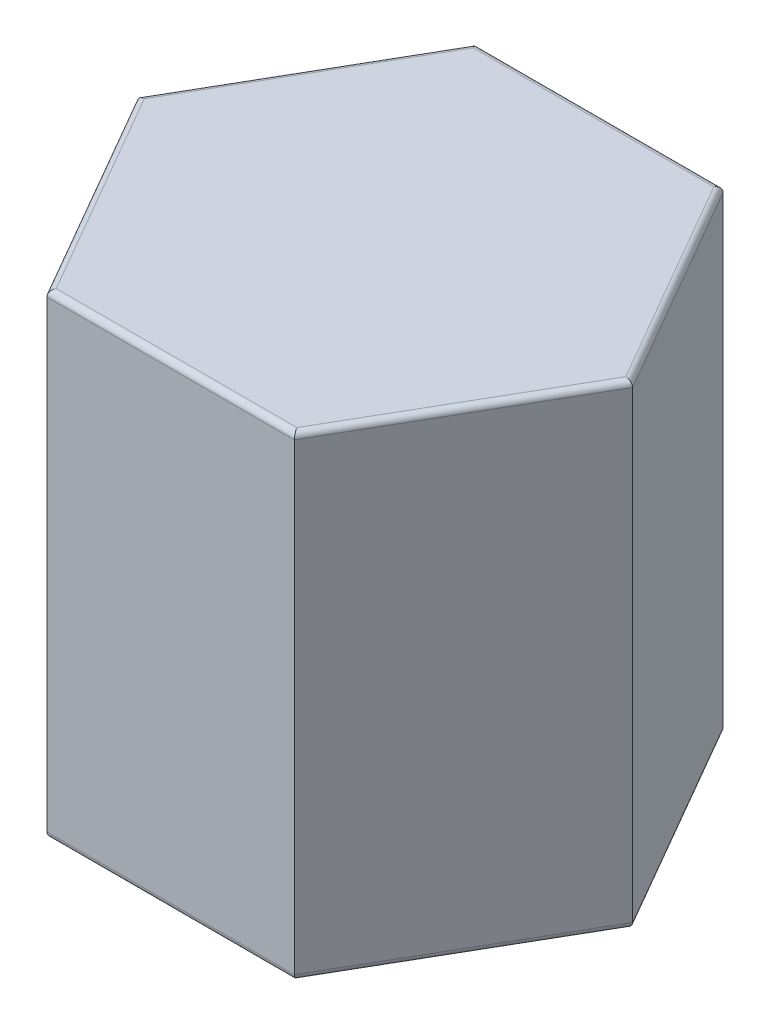
SolidWorks part; units mm, degrees
ref_plane "Front Plane" through (0, 0, 0) normal (1, 0, 0) x (0, 1, 0)
ref_plane "Top Plane" through (0, 0, 0) normal (0, 0, 1) x (0, 1, 0)
ref_plane "Right Plane" through (0, 0, 0) normal (0, 1, 0) x (-1, 0, 0)
sketch "Sketch1" plane through (0, 0, 0) normal (0, 1, 0) x (-1, 0, 0)
  line L0 (-10.4236, 18.0542) -> (10.4217, 18.0542)
  line L1 (10.4217, 18.0542) -> (20.8443, 0.0016)
  line L2 (20.8443, 0.0016) -> (10.4217, -18.0509)
  line L3 (10.4217, -18.0509) -> (-10.4236, -18.0509)
  line L4 (-10.4236, -18.0509) -> (-20.8463, 0.0016)
  line L5 (-20.8463, 0.0016) -> (-10.4236, 18.0542)
extrude "Boss-Extrude1" add sketch "Sketch1" along normal blind 40
fillet "Fillet1" radius 0.5 12 edges at (15.6349, 0, 9.0279) (15.6349, 0, -9.0246) (0.001, 0, -18.0509) (-15.633, 0, -9.0246) (-15.633, 0, 9.0279) (0.001, 0, 18.0542) (15.6349, 40, 9.0279) (15.6349, 40, -9.0246) (0.001, 40, -18.0509) (-15.633, 40, -9.0246) (-15.633, 40, 9.0279) (0.001, 40, 18.0542)
